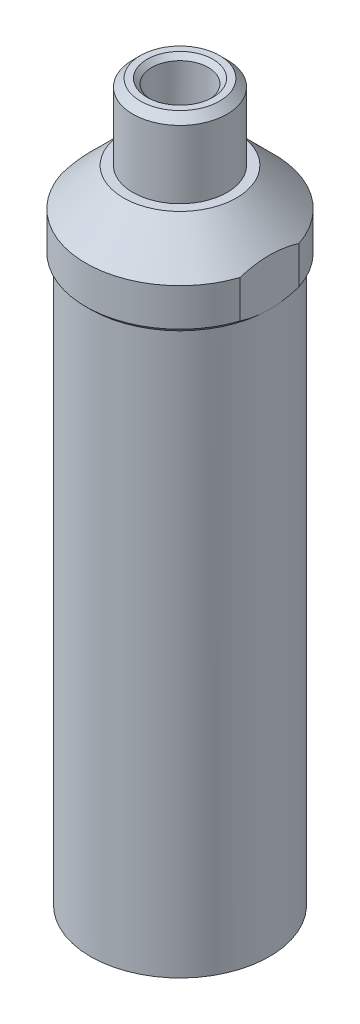
SolidWorks part; units mm, degrees
other "Detailelement1"
material "1.4404 (X2CrNiMo17-12-2"
ref_plane "Vorne" through (0, 0, 0) normal (0, 0, 1) x (1, 0, 0)
ref_plane "Oben" through (0, 0, 0) normal (0, 1, 0) x (1, 0, 0)
ref_plane "Rechts" through (0, 0, 0) normal (1, 0, 0) x (0, 0, -1)
sketch "Skizze2" plane through (0, 0, 0) normal (1, 0, 0) x (0, 0, -1)
  line L0 (0, 40.4227) -> (0, -40.4227) construction
  line L1 (3, 38) -> (3, -38)
  line L2 (3, -38) -> (9.5, -38)
  line L3 (9.5, -38) -> (9.5, 21.5)
  line L4 (10, 22) -> (10, 26)
  line L5 (6, 30) -> (5, 30)
  line L6 (3, 0) -> (0, 0) construction
  line L7 (5, 30) -> (5, 37.2)
  line L8 (5, 37.2) -> (4.2, 38)
  line L9 (4.2, 38) -> (3, 38)
  line L10 (9.5, 21.5) -> (10, 22)
  line L11 (6, 30) -> (10, 26)
  dimension "D2" = 6
  dimension "D3" = 20
  dimension "D4" = 68
  dimension "D5" = 8
  dimension "D6" = 0.8
  dimension "D7" = 45
  dimension "D8" = 10
  dimension "D9" = 8
  dimension "D10" = 76
  dimension "D11" = 45
  dimension "D12" = 19
  dimension "D13" = 12
  dimension "D14" = 45
revolve "Rotation1" add sketch "Skizze2" angle 360 about L0
cosmetic thread "Gewindedarstellung1" parameters "D1"=8, "D2"=8.891
sketch "Skizze3" plane through (0, 30, 0) normal (0, 1, 0) x (1, 0, 0)
  line L0 (0, 0) -> (0, 17.7856) construction
  line L1 (14.5, 11.5) -> (9.5, 11.5)
  line L2 (14.5, 11.5) -> (14.5, -11.5)
  line L3 (14.5, -11.5) -> (9.5, -11.5)
  line L4 (9.5, 11.5) -> (9.5, -11.5)
  line L5 (-9.5, 11.5) -> (-9.5, -11.5)
  line L6 (-14.5, -11.5) -> (-9.5, -11.5)
  line L7 (-14.5, 11.5) -> (-14.5, -11.5)
  line L8 (-14.5, 11.5) -> (-9.5, 11.5)
  line L9 (9.5, 0) -> (0, 0) construction
  dimension "D1" = 19
  dimension "D2" = 5
  dimension "D3" = 23
extrude "Schnitt-Linear austragen1" cut sketch "Skizze3" against normal blind 9
chamfer "Fase1" distance 0.5 angle 45 1 edges at (0, 38, 3)
